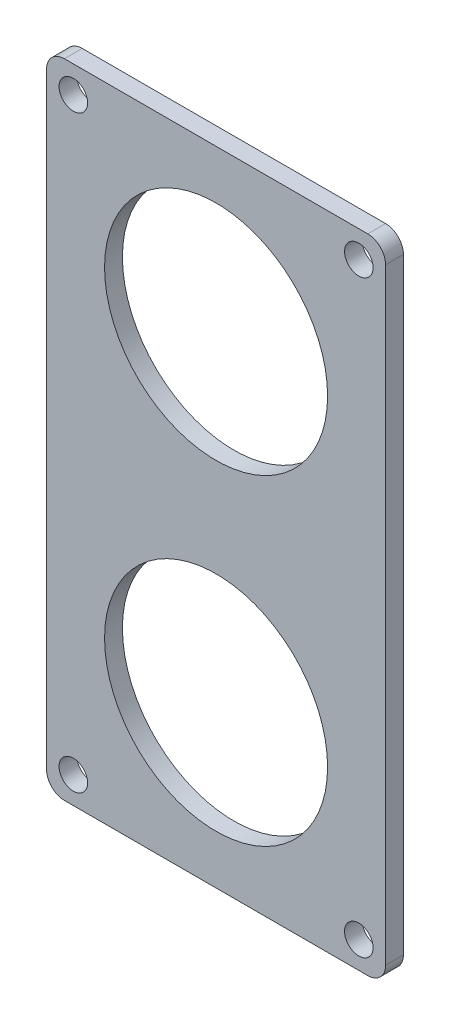
SolidWorks part; units mm, degrees
ref_plane "Front Plane" through (0, 0, 0) normal (0, 0, 1) x (1, 0, 0)
ref_plane "Top Plane" through (0, 0, 0) normal (0, 1, 0) x (1, 0, 0)
ref_plane "Right Plane" through (0, 0, 0) normal (1, 0, 0) x (0, 0, -1)
sketch "Sketch1" plane through (0, 0, 0) normal (0, 0, 1) x (1, 0, 0)
  line L1 (20.5, -17.7) -> (-17.5, -17.7)
  line L2 (20.5, -17.7) -> (20.5, 54.3)
  line L3 (20.5, 54.3) -> (-17.5, 54.3)
  line L4 (-17.5, -17.7) -> (-17.5, 54.3)
  circle A0 centre (17.5, -14.7) radius 1.6
  circle A1 centre (-14.5, -14.7) radius 1.6
  circle A2 centre (17.5, 51.3) radius 1.6
  circle A3 centre (-14.5, 51.3) radius 1.6
  dimension "D2" = 3.2
  dimension "D3" = 3
  dimension "D1" = 72
  dimension "D4" = 3
  dimension "D5" = 3
  dimension "D6" = 3
  dimension "D7" = 38
extrude "Boss-Extrude1" add sketch "Sketch1" along normal blind 2
sketch "Sketch2" plane through (0, 0, 2) normal (0, 0, 1) x (1, 0, 0)
  line L2 (-17.5, 54.3) -> (-17.5, -17.7) construction
  line L10 (20.5, 54.3) -> (-17.5, 54.3) construction
  circle A0 centre (1.5, 0.3) radius 12.5
  circle A1 centre (1.5, 36.3) radius 12.5
  dimension "D1" = 25
  dimension "D2" = 25
  dimension "D3" = 19
  dimension "D4" = 19
  dimension "D5" = 36
  dimension "D6" = 18
extrude "Cut-Extrude1" cut sketch "Sketch2" against normal through all
fillet "Fillet2" radius 2 4 edges at (-17.5, 54.3, 1) (-17.5, -17.7, 1) (20.5, -17.7, 1) (20.5, 54.3, 1)
